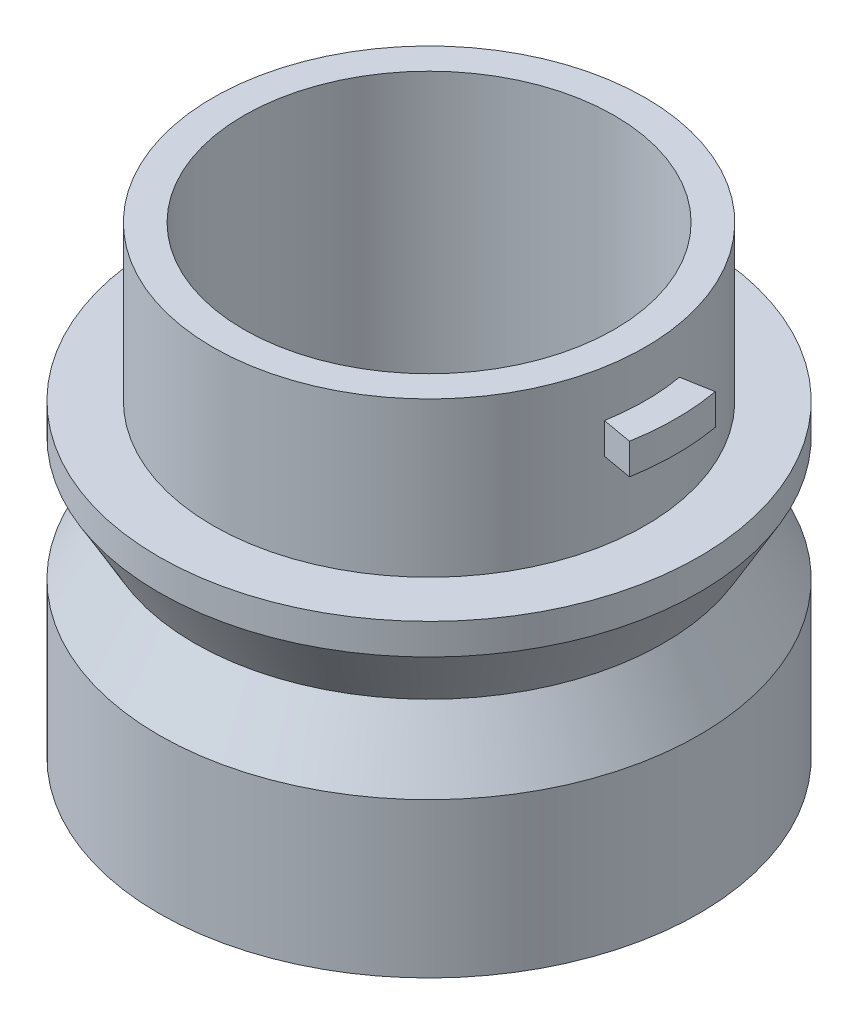
SolidWorks part; units mm, degrees
ref_plane "Front Plane" through (0, 0, 0) normal (0, 0, 1) x (1, 0, 0)
ref_plane "Top Plane" through (0, 0, 0) normal (0, 1, 0) x (1, 0, 0)
ref_plane "Right Plane" through (0, 0, 0) normal (1, 0, 0) x (0, 0, -1)
sketch "Sketch1" plane through (0, 0, 0) normal (0, 0, 1) x (1, 0, 0)
  line L0 (0, 40.4677) -> (0, -47.133) construction
  line L1 (12, 15) -> (12, -5)
  line L2 (14.5, -15) -> (17.5, -15)
  line L3 (17.5, -15) -> (17.5, -5)
  line L4 (17.5, -5) -> (15.1906, -1)
  line L5 (14, 5) -> (14, 15)
  line L6 (14, 15) -> (12, 15)
  line L7 (12, -5) -> (14.5, -5)
  line L8 (14.5, -5) -> (14.5, -15)
  line L9 (-38.6492, 0) -> (68.272, 0) construction
  line L10 (14, 5) -> (17.5, 5)
  line L11 (17.5, 5) -> (17.5, 3)
  line L12 (17.5, 3) -> (15.1906, -1)
  dimension "D1" = 3
  dimension "D2" = 0.5
  dimension "D3" = 12
  dimension "D4" = 2
  dimension "D5" = 10
  dimension "D6" = 210
  dimension "D7" = 20
  dimension "D8" = 10
  dimension "D9" = 210
  dimension "D10" = 2
revolve "Revolve1" add sketch "Sketch1" angle 360 about L0
ref_axis "Axis1" through (0, -42.0041, 0) along (0, 1, 0)
sketch "Sketch2" plane through (0, 0, 0) normal (0, 0, 1) x (1, 0, 0)
  line L0 (14, 12) -> (16, 12)
  line L1 (14, 5) -> (14, 15) construction
  line L2 (16, 12) -> (16, 10)
  line L3 (16, 10) -> (14, 10)
  line L4 (14, 10) -> (14, 12)
  line L5 (-14, 12) -> (-14, 10)
  line L6 (-14, 15) -> (-14, 5) construction
  line L7 (-14, 10) -> (-16, 10)
  line L8 (-16, 10) -> (-16, 12)
  line L9 (-16, 12) -> (-14, 12)
  line L10 (0, 45.3067) -> (0, -45.5409) construction
  line L11 (14, 15) -> (-14, 15) construction
  dimension "D1" = 2
  dimension "D3" = 2
  dimension "D4" = 3
revolve "Revolve2" add sketch "Sketch2" angle 20 mid plane about L10
sketch "Sketch3" plane through (0, 0, 0) normal (0, 0, 1) x (1, 0, 0)
  line L1 (-16.7, -8.2) -> (-14.5, -8.2)
  line L2 (-16.7, -8.2) -> (-16.7, -15)
  line L3 (-16.7, -15) -> (-14.5, -15)
  line L4 (-14.5, -8.2) -> (-14.5, -15)
  line L5 (-17.5, -15) -> (17.5, -15) construction
  line L6 (-17.5, -5) -> (-17.5, -15) construction
  line L7 (16.7, -15) -> (14.5, -15)
  line L8 (16.7, -15) -> (16.7, -8.2)
  line L9 (16.7, -8.2) -> (14.5, -8.2)
  line L10 (14.5, -15) -> (14.5, -8.2)
  line L14 (0, -11.0207) -> (0, -43.2503) construction
  line L15 (-14.5, -5) -> (14.5, -5) construction
  dimension "D2" = 3.2
  dimension "D3" = 0.8
revolve "Cut-Revolve1" cut sketch "Sketch3" angle 25 mid plane about L14
sketch "Sketch4" plane through (0, 0, 0) normal (0, 0, 1) x (1, 0, 0)
  line L1 (-16.7, -8.2) -> (-16.7, -10.7)
  line L2 (-16.7, -8.2) -> (-16.7, -15) construction
  line L3 (-16.7, -10.7) -> (-12, -10.7)
  line L4 (16.7, -15) -> (16.7, -8.2) construction
  line L6 (16.7, -10.7) -> (16.7, -8.2)
  line L7 (16.7, -8.2) -> (12, -8.2)
  line L8 (-12, -10.7) -> (-12, -8.2)
  line L9 (12, -8.2) -> (12, -10.7)
  line L10 (12, -10.7) -> (16.7, -10.7)
  line L11 (-12, -8.2) -> (-16.7, -8.2)
  dimension "D1" = 2.5
revolve "Cut-Revolve2" cut sketch "Sketch4" angle 45 about axis through (0, -42.0041, 0) along (0, 1, 0)
